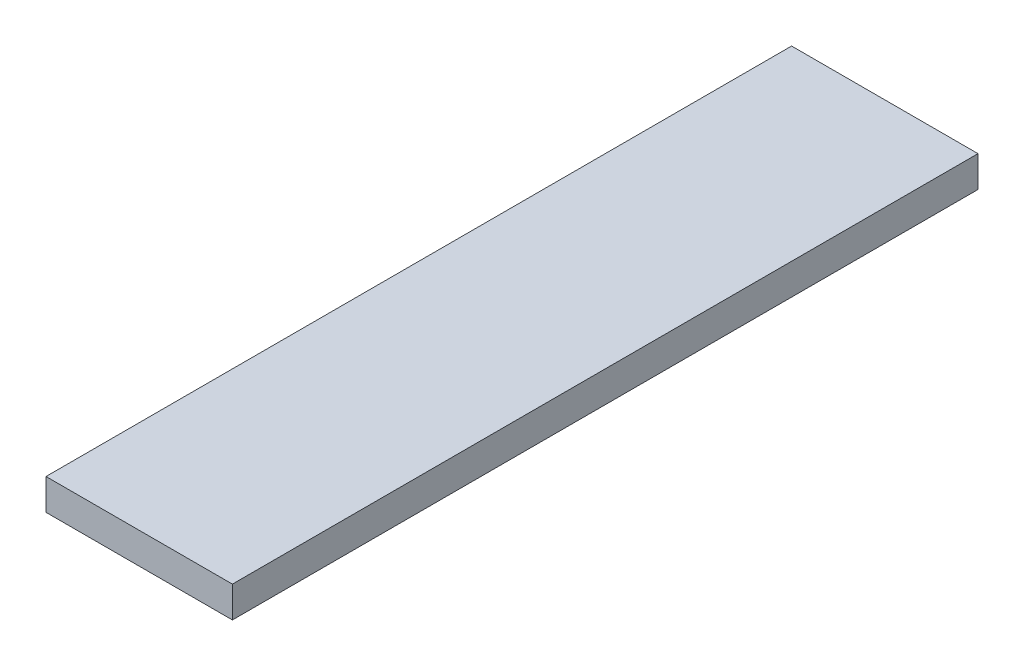
SolidWorks part; units mm, degrees
material "Polyurethane Foam Flexible"
ref_plane "Front Plane" through (0, 0, 0) normal (0, 0, 1) x (1, 0, 0)
ref_plane "Top Plane" through (0, 0, 0) normal (0, 1, 0) x (1, 0, 0)
ref_plane "Right Plane" through (0, 0, 0) normal (1, 0, 0) x (0, 0, -1)
sketch "Sketch1" plane through (0, 0, 0) normal (0, 1, 0) x (1, 0, 0)
  line L1 (19.05, -76.2) -> (-19.05, -76.2)
  line L2 (19.05, -76.2) -> (19.05, 76.2)
  line L3 (19.05, 76.2) -> (-19.05, 76.2)
  line L4 (-19.05, -76.2) -> (-19.05, 76.2)
  line L5 (19.05, -76.2) -> (-19.05, 76.2) construction
  line L6 (19.05, 76.2) -> (-19.05, -76.2) construction
  point P0 (0, 0)
  dimension "D1" = 152.4
  dimension "D2" = 38.1
extrude "Boss-Extrude1" add sketch "Sketch1" along normal blind 6.35
sketch "Sketch2" plane through (0, 6.35, 0) normal (0, 1, 0) x (1, 0, 0)
  line L4 (-12.7, 0) -> (12.7, 0) construction
  line L5 (19.05, -76.2) -> (19.05, 76.2) construction
  line L6 (19.05, 76.2) -> (-19.05, 76.2) construction
  line L7 (-19.05, 76.2) -> (-19.05, -76.2) construction
  circle A0 centre (-12.7, 69.85) radius 2.4638
  circle A1 centre (12.7, 69.85) radius 2.4638
  circle A2 centre (12.7, 50.8) radius 2.4638
  circle A3 centre (-12.7, 50.8) radius 2.4638
  circle A4 centre (-12.7, 25.4) radius 2.4638
  circle A5 centre (12.7, 25.4) radius 2.4638
  circle A6 centre (-12.7, 0) radius 2.4638
  circle A7 centre (12.7, 0) radius 2.4638
  circle A8 centre (-12.7, -25.4) radius 2.4638
  circle A9 centre (12.7, -25.4) radius 2.4638
  circle A10 centre (-12.7, -50.8) radius 2.4638
  circle A11 centre (12.7, -50.8) radius 2.4638
  circle A12 centre (12.7, -69.85) radius 2.4638
  circle A13 centre (-12.7, -69.85) radius 2.4638
  dimension "D1" = 4.9276
  dimension "D2" = 4.9276
  dimension "D3" = 4.9276
  dimension "D4" = 4.9276
  dimension "D6" = 25.4
  dimension "D8" = 25.4
  dimension "D9" = 25.4
  dimension "D10" = 6.35
  dimension "D7" = 6.35
  dimension "D5" = 5
extrude "Cut-Extrude1" [suppressed] cut sketch "Sketch2" against normal through all both and the other way through all
